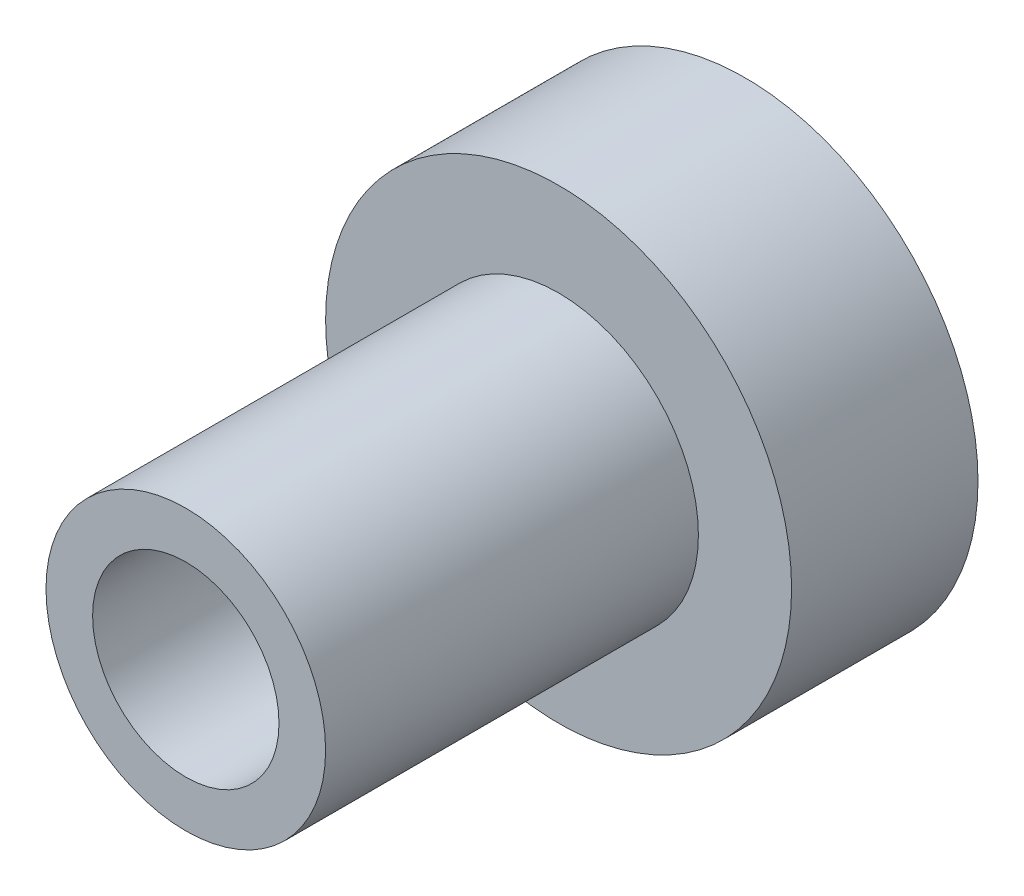
SolidWorks part; units mm, degrees
ref_plane "Alzado" through (0, 0, 0) normal (0, 0, 1) x (1, 0, 0)
ref_plane "Planta" through (0, 0, 0) normal (0, 1, 0) x (1, 0, 0)
ref_plane "Vista lateral" through (0, 0, 0) normal (1, 0, 0) x (0, 0, -1)
sketch "Croquis1" plane through (0, 0, 0) normal (0, 0, 1) x (1, 0, 0)
  circle A0 centre (0, 0) radius 25
extrude "Saliente-Extruir1" add sketch "Croquis1" along normal blind 20
sketch "Croquis2" plane through (0, 0, 20) normal (0, 0, 1) x (1, 0, 0)
  circle A0 centre (0, 0) radius 15
extrude "Saliente-Extruir2" add sketch "Croquis2" along normal blind 40 and the other way blind 1
sketch "Croquis3" plane through (0, 0, 60) normal (0, 0, 1) x (1, 0, 0)
  circle A0 centre (0, 0) radius 10
extrude "Cortar-Extruir1" cut sketch "Croquis3" against normal blind 40
